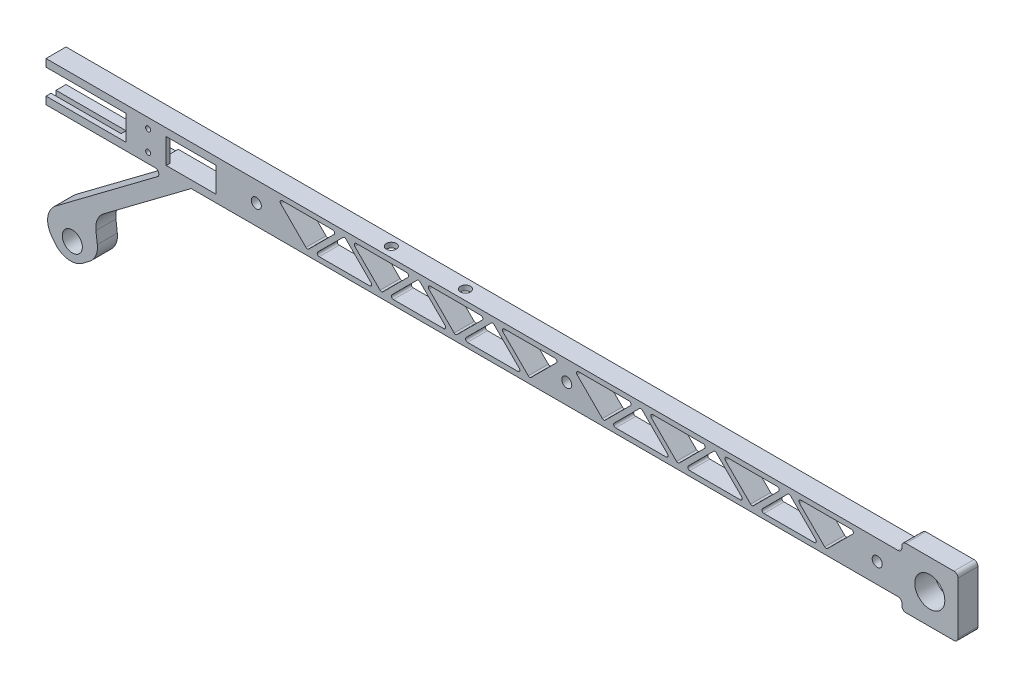
SolidWorks part; units mm, degrees
material "Magnesium Alloy"
ref_plane "Front Plane" through (0, 0, 0) normal (0, 0, 1) x (1, 0, 0)
ref_plane "Top Plane" through (0, 0, 0) normal (0, 1, 0) x (1, 0, 0)
ref_plane "Right Plane" through (0, 0, 0) normal (1, 0, 0) x (0, 0, -1)
sketch "Sketch1" plane through (0, 0, 0) normal (0, 0, 1) x (1, 0, 0)
  line L0 (2.54, 0) -> (568.96, 0)
  line L1 (571.5, 2.54) -> (571.5, 22.86)
  line L2 (568.96, 25.4) -> (2.54, 25.4)
  line L3 (0, 22.86) -> (0, 2.54)
  line L4 (0, 22.86) -> (0, 25.4)
  line L5 (0, 25.4) -> (2.54, 25.4)
  line L6 (0, 2.54) -> (0, 0)
  line L7 (0, 0) -> (2.54, 0)
  arc A1 (568.96, 25.4) -> (571.5, 22.86) centre (568.96, 22.86) cw
  arc A2 (571.5, 2.54) -> (568.96, 0) centre (568.96, 2.54) cw
  point P7 (0, 25.4)
  point P12 (571.5, 0)
  point P15 (0, 0)
  dimension "D3" = 2.54
  dimension "D1" = 571.5
  dimension "D2" = 25.4
extrude "Boss-Extrude1" add sketch "Sketch1" along normal blind 12.7
sketch "Sketch2" plane through (0, 0, 0) normal (0, 0, 1) x (1, 0, 0)
  line L0 (173.2461, 3.175) -> (205.2139, 3.175)
  line L1 (206.112, 5.343) -> (190.128, 21.327)
  line L2 (188.332, 21.327) -> (172.348, 5.343)
  line L3 (0, 0) -> (568.96, 0) construction
  line L4 (0, 25.4) -> (0, 0) construction
  arc A0 (188.332, 21.327) -> (190.128, 21.327) centre (189.23, 20.4289) cw
  arc A1 (206.112, 5.343) -> (205.2139, 3.175) centre (205.2139, 4.445) cw
  arc A2 (173.2461, 3.175) -> (172.348, 5.343) centre (173.2461, 4.445) cw
  point P9 (189.23, 22.225)
  point P12 (208.28, 3.175)
  point P15 (170.18, 3.175)
  dimension "D5" = 1.27
  dimension "D1" = 38.1
  dimension "D2" = 19.05
  dimension "D3" = 3.175
  dimension "D4" = 170.18
extrude "Cut-Extrude1" cut sketch "Sketch2" along normal blind 12.7
pattern_linear "LPattern1" count 7 spacing 46.99 along (1, 0, 0) skipping (3, 0) of "Cut-Extrude1"
sketch "Sketch3" plane through (0, 0, 0) normal (0, 0, 1) x (1, 0, 0)
  line L0 (149.7511, 22.225) -> (181.7189, 22.225)
  line L1 (182.617, 20.057) -> (166.633, 4.073)
  line L2 (164.837, 4.073) -> (148.853, 20.057)
  line L3 (568.96, 25.4) -> (0, 25.4) construction
  line L4 (0, 25.4) -> (0, 0) construction
  arc A0 (164.837, 4.073) -> (166.633, 4.073) centre (165.735, 4.9711) ccw
  arc A1 (182.617, 20.057) -> (181.7189, 22.225) centre (181.7189, 20.955) ccw
  arc A2 (149.7511, 22.225) -> (148.853, 20.057) centre (149.7511, 20.955) ccw
  point P9 (165.735, 3.175)
  point P12 (184.785, 22.225)
  point P15 (146.685, 22.225)
  dimension "D5" = 1.27
  dimension "D1" = 38.1
  dimension "D2" = 19.05
  dimension "D3" = 3.175
  dimension "D4" = 146.685
extrude "Cut-Extrude2" cut sketch "Sketch3" along normal blind 12.7
pattern_linear "LPattern2" count 8 spacing 46.99 along (1, 0, 0) of "Cut-Extrude2"
ref_plane "Plane1" through (292.1, 0, 0) normal (1, 0, 0) x (0, 0, -1)
sketch "Sketch8" plane through (0, 0, 0) normal (0, 0, 1) x (1, 0, 0)
  line L0 (92.075, 0) -> (-9.525, -76.2)
  line L1 (0, 0) -> (568.96, 0) construction
  line L2 (-9.525, -76.2) -> (-15.24, -68.58)
  line L3 (-15.24, -68.58) -> (76.2, 0)
  line L4 (76.2, 0) -> (92.075, 0)
  line L5 (0, 25.4) -> (0, 0) construction
  dimension "D1" = 76.2
  dimension "D2" = 101.6
  dimension "D3" = 9.525
  dimension "D4" = 76.2
extrude "Boss-Extrude3" add sketch "Sketch8" along normal blind 12.7
hole_wizard "Ø5.0mm Dowel Hole1" positions "Sketch9" profile "Sketch10" hole size "Ø5.0" standard "ANSI Metric"
sketch "Sketch9" plane through (33.147, -44.196, 0) normal (0.6, -0.8, 0) x (-0.8, -0.6, 0)
  line L0 (53.34, -12.7) -> (53.34, 0) construction
  line L1 (53.34, 0) -> (-73.66, 0) construction
  point P0 (46.99, -6.35)
  dimension "D1" = 6.35
  dimension "D2" = 6.35
sketch "Sketch10" plane through (-4.445, -72.39, 6.35) normal (0, 0, 1) x (0.8, 0.6, 0)
  line L0 (0, 0) -> (0, 11.0272)
  line L1 (0, 11.0272) -> (2.5, 9.525)
  line L2 (2.5, 9.525) -> (2.5, 0)
  line L5 (2.5, 0) -> (0, 0)
  line L10 (0, 11.0272) -> (-2.5, 9.525) construction
  line L11 (0, -6.35) -> (0, 107.95) construction
  dimension "Hole Dia." = 5
  dimension "Hole Depth" = 9.525
  dimension "Drill Angle" = 118
thread "Thread1" pitch 0.8 start angle 0, offset 0, length 8.8138, pitch 0.8, diameter 5
ref_plane "Plane2" through (-2.445, -70.89, 6.35) normal (0, 0, 1) x (0.8, 0.6, 0)
sketch "Thread Profile1" plane through (-2.445, -70.89, 6.35) normal (0, 0, 1) x (0.8, 0.6, 0)
  line L0 (0, 0) -> (0, 0.8) construction
  line L11 (0, 0) -> (0, 0.7)
  line L12 (0, 0.7) -> (-0.433, 0.45)
  line L13 (-0.433, 0.45) -> (-0.433, 0.25)
  line L15 (-0.433, 0.25) -> (0, 0)
  line L17 (-0.433, 0.35) -> (0, 0.35) construction
  point P2 (0, 0)
  dimension "Pitch" = 0.8
  dimension "Profile_Angle" = 60
  dimension "Profile_Land" = 0.2
  dimension "Profile_Height" = 0.433
sketch "Sketch14" plane through (0, 0, 0) normal (0, 0, -1) x (-1, 0, 0)
  line L0 (-571.5, 2.54) -> (-571.5, 22.86) construction
  line L1 (-92.075, 0) -> (-568.96, 0) construction
  circle A0 centre (-560.3875, 12.7) radius 3.175
  dimension "D1" = 6.35
  dimension "D2" = 11.1125
  dimension "D3" = 12.7
extrude "Cut-Extrude5" cut sketch "Sketch14" against normal through all
sketch "Sketch15" plane through (0, 0, 12.7) normal (0, 0, 1) x (1, 0, 0)
  line L0 (0, 20.6375) -> (50.8, 20.6375)
  line L1 (0, 25.4) -> (0, 0) construction
  line L2 (50.8, 20.6375) -> (50.8, 4.7625)
  line L3 (50.8, 4.7625) -> (0, 4.7625)
  line L4 (0, 4.7625) -> (0, 20.6375)
  line L5 (568.96, 25.4) -> (0, 25.4) construction
  dimension "D1" = 15.875
  dimension "D2" = 50.8
  dimension "D3" = 4.7625
extrude "Cut-Extrude6" cut sketch "Sketch15" against normal through all
sketch "Sketch16" plane through (0, 0, 0) normal (-1, 0, 0) x (0, 0, 1)
  line L0 (6.35, 23.8125) -> (9.525, 23.8125)
  line L1 (9.525, 23.8125) -> (9.525, 1.5875)
  line L2 (9.525, 1.5875) -> (6.35, 1.5875)
  line L3 (6.35, 1.5875) -> (6.35, 23.8125)
  line L7 (12.7, 0) -> (0, 0) construction
  line L8 (12.7, 25.4) -> (12.7, 20.6375) construction
  dimension "D1" = 3.175
  dimension "D2" = 3.175
  dimension "D3" = 22.225
  dimension "D4" = 1.5875
extrude "Cut-Extrude7" cut sketch "Sketch16" against normal blind 44.45
sketch "Sketch17" plane through (0, 0, 0) normal (0, 0, 1) x (1, 0, 0)
  line L0 (50.8, 20.6375) -> (54.61, 20.6375)
  line L1 (107.95, 20.6375) -> (107.95, 4.7625)
  line L2 (107.95, 4.7625) -> (71.12, 4.7625)
  line L3 (50.8, 4.7625) -> (50.8, 20.6375)
  line L4 (54.61, 20.6375) -> (55.88, 22.2885)
  line L5 (55.88, 22.2885) -> (71.12, 22.2885)
  line L6 (71.12, 22.2885) -> (71.12, 20.6375)
  line L7 (71.12, 4.7625) -> (71.12, 3.1115)
  line L8 (71.12, 3.1115) -> (55.88, 3.1115)
  line L9 (55.88, 3.1115) -> (54.61, 4.7625)
  line L10 (54.61, 4.7625) -> (50.8, 4.7625)
  line L11 (71.12, 20.6375) -> (107.95, 20.6375)
  point P15 (52.705, 4.7625)
  dimension "D1" = 57.15
  dimension "D2" = 15.24
  dimension "D3" = 16.51
  dimension "D4" = 1.651
  dimension "D5" = 1.651
  dimension "D6" = 3.81
  dimension "D7" = 3.81
  dimension "D8" = 5.08
extrude "Cut-Extrude8" cut sketch "Sketch17" along normal blind 10.16
sketch "Sketch18" plane through (0, 0, 10.16) normal (0, 0, -1) x (-1, 0, 0)
  line L0 (-107.95, 4.7625) -> (-76.2, 4.7625)
  line L1 (-71.12, 4.7625) -> (-107.95, 4.7625) construction
  line L2 (-76.2, 4.7625) -> (-76.2, 20.6375)
  line L3 (-107.95, 20.6375) -> (-71.12, 20.6375) construction
  line L4 (-76.2, 20.6375) -> (-107.95, 20.6375)
  line L5 (-107.95, 20.6375) -> (-107.95, 4.7625)
  dimension "D1" = 31.75
extrude "Cut-Extrude9" cut sketch "Sketch18" against normal blind 2.54
hole_wizard "1/8 (0.125) Diameter Hole1" positions "Sketch19" profile "Sketch20" hole size "1/8" standard "ANSI Inch" end condition through all
sketch "Sketch19" plane through (0, 0, 10.16) normal (0, 0, -1) x (-1, 0, 0)
  line L0 (-76.2, 4.7625) -> (-76.2, 20.6375) construction
  line L1 (-71.12, 22.2885) -> (-55.88, 22.2885) construction
  line L2 (-55.88, 3.1115) -> (-71.12, 3.1115) construction
  point P0 (-64.77, 19.1135)
  point P2 (-64.77, 6.2865)
  dimension "D1" = 11.43
  dimension "D2" = 3.175
  dimension "D3" = 11.43
  dimension "D4" = 3.175
sketch "Sketch20" plane through (64.77, 19.1135, 10.16) normal (1, 0, 0) x (0, 1, 0)
  line L0 (0, 0) -> (0, 2.54)
  line L1 (0, 2.54) -> (1.5875, 2.54)
  line L2 (1.5875, 2.54) -> (1.5875, 0)
  line L5 (1.5875, 0) -> (0, 0)
  line L11 (0, -6.35) -> (0, 107.95) construction
  dimension "Thru Hole Dia." = 3.175
  dimension "Thru Hole Depth" = 2.54
thread "Thread2" pitch 0.635 start angle 0, offset 0, length 1.9812, pitch 0.635, diameter 3.175
ref_plane "Plane3" through (66.3575, 19.1135, 10.16) normal (0, -1, 0) x (1, 0, 0)
sketch "Thread Profile2" plane through (66.3575, 19.1135, 10.16) normal (0, -1, 0) x (1, 0, 0)
  line L0 (0, 0) -> (0, 0.635) construction
  line L11 (0, 0) -> (0, 0.5556)
  line L12 (0, 0.5556) -> (-0.3437, 0.3572)
  line L13 (-0.3437, 0.3572) -> (-0.3437, 0.1984)
  line L15 (-0.3437, 0.1984) -> (0, 0)
  line L17 (-0.3437, 0.2778) -> (0, 0.2778) construction
  point P2 (0, 0)
  dimension "Pitch" = 0.635
  dimension "Profile_Angle" = 60
  dimension "Profile_Land" = 0.1588
  dimension "Profile_Height" = 0.3437
thread "Thread3" pitch 0.635 start angle 0, offset 0, length 1.9812, pitch 0.635, diameter 3.175
ref_plane "Plane4" through (66.3575, 6.2865, 10.16) normal (0, -1, 0) x (1, 0, 0)
sketch "Thread Profile3" plane through (66.3575, 6.2865, 10.16) normal (0, -1, 0) x (1, 0, 0)
  line L0 (0, 0) -> (0, 0.635) construction
  line L11 (0, 0) -> (0, 0.5556)
  line L12 (0, 0.5556) -> (-0.3437, 0.3572)
  line L13 (-0.3437, 0.3572) -> (-0.3437, 0.1984)
  line L15 (-0.3437, 0.1984) -> (0, 0)
  line L17 (-0.3437, 0.2778) -> (0, 0.2778) construction
  point P2 (0, 0)
  dimension "Pitch" = 0.635
  dimension "Profile_Angle" = 60
  dimension "Profile_Land" = 0.1588
  dimension "Profile_Height" = 0.3437
sketch "Sketch21" plane through (0, 0, 0) normal (0, 0, -1) x (-1, 0, 0)
  line L0 (-76.2, 0) -> (-69.85, 0)
  line L1 (0, 0) -> (-76.2, 0) construction
  line L3 (-76.2, 0) -> (15.24, -68.58) construction
  line L4 (-71.12, -3.81) -> (-76.2, 0)
  arc A0 (-71.12, -3.81) -> (-69.85, 0) centre (-69.0094, -2.3969) cw
  dimension "D1" = 2.54
  dimension "D2" = 6.35
extrude "Boss-Extrude4" add sketch "Sketch21" against normal blind 12.7
hole_wizard "1/4 (0.25) Diameter Hole1" positions "Sketch22" profile "Sketch23" hole size "1/4" standard "ANSI Inch" end condition through all
sketch "Sketch22" plane through (0, 0, 12.7) normal (0, 0, 1) x (1, 0, 0)
  line L0 (568.96, 25.4) -> (0, 25.4) construction
  line L1 (107.95, 20.6375) -> (107.95, 4.7625) construction
  point P0 (133.35, 12.7)
  point P2 (330.2, 12.7)
  point P4 (527.05, 12.7)
  dimension "D1" = 12.7
  dimension "D2" = 25.4
  dimension "D3" = 12.7
  dimension "D4" = 222.25
  dimension "D5" = 12.7
  dimension "D6" = 419.1
sketch "Sketch23" plane through (133.35, 12.7, 12.7) normal (1, 0, 0) x (0, -1, 0)
  line L0 (0, 0) -> (0, 12.7)
  line L1 (0, 12.7) -> (3.175, 12.7)
  line L2 (3.175, 12.7) -> (3.175, 0)
  line L5 (3.175, 0) -> (0, 0)
  line L11 (0, -6.35) -> (0, 107.95) construction
  dimension "Thru Hole Dia." = 6.35
  dimension "Thru Hole Depth" = 12.7
hole_wizard "1/4 (0.25) Diameter Hole2" positions "Sketch24" profile "Sketch25" hole size "1/4" standard "ANSI Inch"
sketch "Sketch24" plane through (0, 25.4, 0) normal (0, 1, 0) x (1, 0, 0)
  line L0 (568.96, 0) -> (0, 0) construction
  line L1 (568.96, -12.7) -> (0, -12.7) construction
  line L2 (196.7411, -12.7) -> (196.7411, 0) construction
  line L5 (243.7311, -12.7) -> (243.7311, 0) construction
  point P2 (212.6161, -6.35)
  point P8 (259.6061, -6.35)
  point P13 (0, 0)
  point P20 (0, 0)
  dimension "D1" = 15.875
  dimension "D2" = 6.35
  dimension "D3" = 15.875
  dimension "D6" = 6.35
sketch "Sketch25" plane through (212.6161, 25.4, 6.35) normal (1, 0, 0) x (0, 0, 1)
  line L0 (0, 0) -> (0, 5.0827)
  line L1 (0, 5.0827) -> (3.175, 3.175)
  line L2 (3.175, 3.175) -> (3.175, 0)
  line L5 (3.175, 0) -> (0, 0)
  line L10 (0, 5.0827) -> (-3.175, 3.175) construction
  line L11 (0, -6.35) -> (0, 107.95) construction
  dimension "Hole Dia." = 6.35
  dimension "Hole Depth" = 3.175
  dimension "Drill Angle" = 118
sketch "Sketch26" plane through (0, 0, 12.7) normal (0, 0, 1) x (1, 0, 0)
  line L0 (-9.525, -76.2) -> (1.651, -67.818)
  line L1 (-9.525, -76.2) -> (92.075, 0) construction
  line L2 (1.651, -67.818) -> (-0.254, -65.278)
  line L3 (-0.254, -65.278) -> (-11.43, -73.66)
  line L4 (-15.24, -68.58) -> (-9.525, -76.2) construction
  line L5 (-11.43, -73.66) -> (-9.525, -76.2)
  line L6 (71.12, -3.81) -> (-15.24, -68.58) construction
  dimension "D1" = 13.97
  dimension "D2" = 6.35
extrude "Cut-Extrude10" cut sketch "Sketch26" against normal up to surface (12.7 mm away) up to face at (136.525, 12.7, 0)
sketch "Sketch28" plane through (0, 0, 12.7) normal (0, 0, 1) x (1, 0, 0)
  line L0 (1.651, -67.818) -> (13.081, -83.058)
  line L1 (13.081, -83.058) -> (33.401, -67.818)
  line L2 (33.401, -67.818) -> (30.7698, -45.9789)
  line L3 (1.651, -67.818) -> (92.075, 0) construction
  line L4 (30.7698, -45.9789) -> (1.651, -67.818)
  circle A0 centre (16.6878, -66.7004) radius 6.35
  dimension "D5" = 12.7
  dimension "D1" = 90
  dimension "D2" = 60
  dimension "D3" = 19.05
  dimension "D4" = 25.4
  dimension "D6" = 8.128
extrude "Boss-Extrude5" add sketch "Sketch28" against normal blind 12.7
sketch "Sketch29" plane through (0, 0, 12.7) normal (0, 0, 1) x (1, 0, 0)
  line L0 (-15.24, -68.58) -> (-11.43, -73.66)
  line L1 (-15.24, -68.58) -> (-4.064, -60.198)
  line L2 (-11.43, -73.66) -> (-0.254, -65.278)
  line L3 (-4.064, -60.198) -> (-0.254, -65.278)
  line L4 (13.081, -83.058) -> (-0.254, -65.278) construction
  dimension "D1" = 0
extrude "Cut-Extrude11" cut sketch "Sketch29" against normal blind 12.7
fillet "Fillet1" radius 12.7 4 edges at (-4.064, -60.198, 6.35) (13.081, -83.058, 6.35) (33.401, -67.818, 6.35) (30.7698, -45.9789, 6.35)
sketch "Sketch30" plane through (0, 0, 12.7) normal (0, 0, 1) x (1, 0, 0)
  line L0 (571.5, 2.54) -> (571.5, 22.86) construction
  line L1 (578.2629, 12.7) -> (578.2629, 31.75)
  line L2 (578.2629, 31.75) -> (542.7029, 31.75)
  line L3 (542.7029, 31.75) -> (542.7029, 25.4)
  line L4 (542.7029, 25.4) -> (542.7029, 0)
  line L5 (92.075, 0) -> (568.96, 0) construction
  line L6 (578.2629, 12.7) -> (578.2629, -6.35)
  line L7 (578.2629, -6.35) -> (542.7029, -6.35)
  line L8 (542.7029, -6.35) -> (542.7029, 0)
  circle A2 centre (560.3875, 12.7) radius 3.175
  dimension "D1" = 6.35
  dimension "D2" = 19.05
  dimension "D3" = 19.05
  dimension "D4" = 6.35
  dimension "D5" = 35.56
  dimension "D6" = 17.8754
  dimension "D7" = 6.7629
extrude "Boss-Extrude7" add sketch "Sketch30" against normal blind 12.7
sketch "Sketch31" plane through (0, 0, 12.7) normal (0, 0, 1) x (1, 0, 0)
  circle A0 centre (560.3875, 12.7) radius 9.525
  dimension "D1" = 19.05
extrude "Cut-Extrude12" cut sketch "Sketch31" against normal blind 12.7
fillet "Fillet2" radius 2.54 2 edges at (578.2629, -6.35, 6.35) (578.2629, 31.75, 6.35)
fillet "Fillet5" radius 2.54 4 edges at (542.7029, 0, 6.35) (542.7029, -6.35, 6.35) (542.7029, 25.4, 6.35) (542.7029, 31.75, 6.35)
